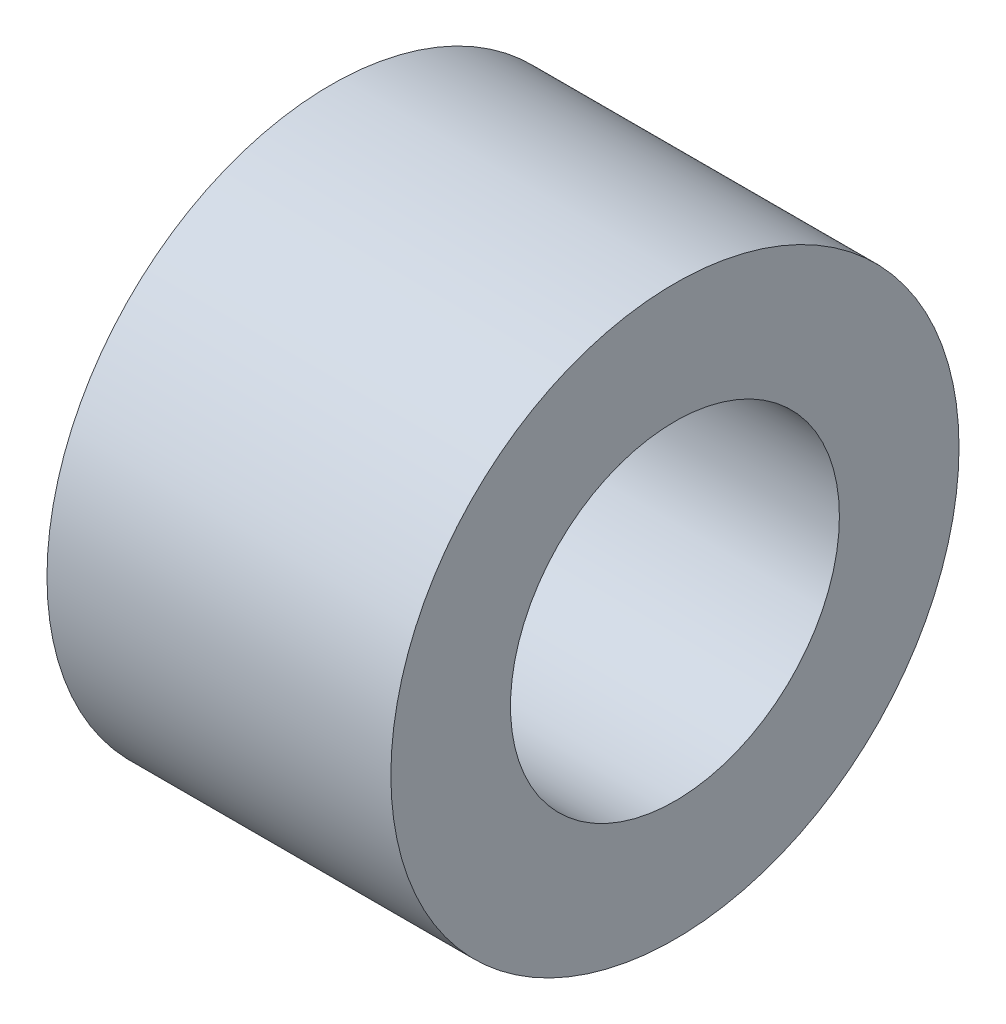
SolidWorks part; units mm, degrees
ref_plane "Alzado" through (0, 0, 0) normal (0, 0, 1) x (1, 0, 0)
ref_plane "Planta" through (0, 0, 0) normal (0, 1, 0) x (1, 0, 0)
ref_plane "Vista lateral" through (0, 0, 0) normal (1, 0, 0) x (0, 0, -1)
sketch "Croquis1" plane through (0, 0, 0) normal (1, 0, 0) x (0, 0, -1)
  circle A0 centre (0, 0) radius 2.75
  circle A1 centre (0, 0) radius 4.75
  dimension "D1" = 5.5
  dimension "D2" = 2
extrude "Saliente-Extruir1" add sketch "Croquis1" along normal blind 5.75
